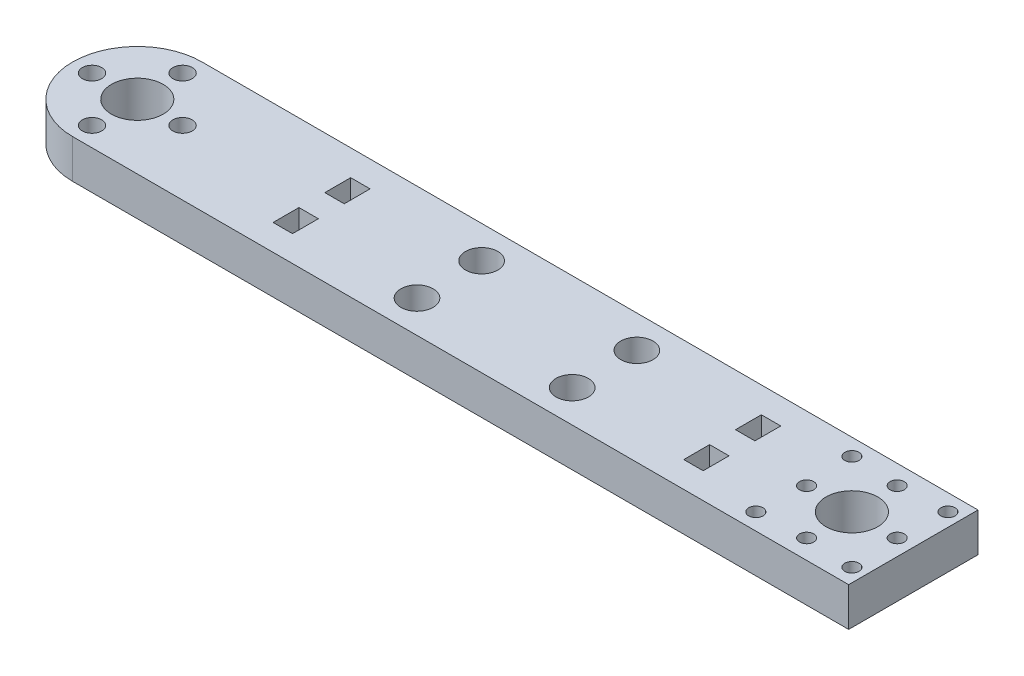
SolidWorks part; units mm, degrees
material "PF"
ref_plane "前视基准面" through (0, 0, 0) normal (0, 0, 1) x (1, 0, 0)
ref_plane "上视基准面" through (0, 0, 0) normal (0, 1, 0) x (1, 0, 0)
ref_plane "右视基准面" through (0, 0, 0) normal (1, 0, 0) x (0, 0, -1)
sketch "草图1" plane through (0, 0, 0) normal (0, 1, 0) x (1, 0, 0)
  line L1 (-41.2, 20) -> (78.8, 20)
  line L3 (-41.2, 0) -> (78.8, 0)
  line L4 (78.8, 20) -> (78.8, 0)
  arc A0 (-41.2, 20) -> (-41.2, 0) centre (-41.2, 10) ccw
  dimension "D1" = 20
  dimension "D2" = 120
extrude "凸台-拉伸1" add sketch "草图1" along normal blind 6
sketch "草图2" plane through (0, 6, 0) normal (0, 1, 0) x (1, 0, 0)
  line L0 (-41.2, 20) -> (-41.2, 0) construction
  line L1 (-41.2, 17) -> (-41.2, 3)
  circle A0 centre (-41.2, 3) radius 1.5
  circle A1 centre (-48.2, 10) radius 1.5
  circle A2 centre (-41.2, 17) radius 1.5
  circle A3 centre (-34.2, 10) radius 1.5
  circle A4 centre (-41.2, 10) radius 4
  point P7 (-41.2, 10)
  dimension "D1" = 4
extrude "切除-拉伸1" cut sketch "草图2" against normal blind 10 contours A1 | A2 L0 L1 | L0 A2 L1 | A3 | L1 L0 A0 | L0 L1 A0 | A4
sketch "草图3" plane through (0, 6, 0) normal (0, 1, 0) x (1, 0, 0)
  line L0 (-51.2, 10) -> (-14.2, 10) construction
  line L1 (-14.2, 20) -> (-14.2, 0) construction
  line L2 (78.8, 20) -> (-41.2, 20) construction
  line L3 (-41.2, 0) -> (78.8, 0) construction
  line L4 (-14.2, 12) -> (-14.2, 8)
  line L5 (-14.2, 12) -> (-14.2, 16)
  line L6 (-14.2, 12) -> (-11.2, 12)
  line L7 (-14.2, 16) -> (-11.2, 16)
  line L8 (-11.2, 12) -> (-11.2, 16)
  line L9 (-14.2, 8) -> (-14.2, 4)
  line L10 (-14.2, 8) -> (-11.2, 8)
  line L11 (-14.2, 4) -> (-11.2, 4)
  line L12 (-11.2, 8) -> (-11.2, 4)
  arc A0 (-41.2, 20) -> (-41.2, 0) centre (-41.2, 10) ccw construction
  circle A1 centre (-41.2, 10) radius 4 construction
  point P14 (-14.2, 10)
  dimension "D4" = 27
  dimension "D1" = 4
  dimension "D2" = 4
  dimension "D3" = 3
extrude "切除-拉伸2" cut sketch "草图3" against normal blind 10 contours L5 L6 L8 L7 | L9 L10 L12 L11
sketch "草图4" plane through (0, 6, 0) normal (0, 1, 0) x (1, 0, 0)
  line L0 (78.8, 10) -> (69.3, 10) construction
  line L1 (78.8, 0) -> (78.8, 20) construction
  line L2 (78.8, 20) -> (78.8, 0)
  line L3 (69.3, 10) -> (76.7246, 17.4246)
  line L4 (69.3, 10) -> (62.3, 10)
  line L5 (69.3, 17) -> (69.3, 3) construction
  line L6 (69.3, 3) -> (69.3, 10) construction
  line L7 (61.8754, 17.4246) -> (69.3, 10) construction
  line L8 (69.3, 10) -> (76.7246, 2.5754) construction
  line L9 (76.7246, 2.5754) -> (69.3, 10) construction
  line L10 (61.8754, 2.5754) -> (69.3, 10) construction
  line L11 (61.8754, 2.5754) -> (69.3, 10) construction
  line L12 (69.3, 10) -> (52.3, 10) construction
  line L13 (52.3, 20) -> (52.3, 0)
  line L14 (-41.2, 0) -> (78.8, 0) construction
  line L15 (52.3, 12) -> (52.3, 16)
  line L16 (52.3, 12) -> (49.3, 12)
  line L17 (52.3, 16) -> (49.3, 16)
  line L18 (49.3, 12) -> (49.3, 16)
  line L19 (-14.2, 12) -> (-11.2, 12) construction
  line L20 (52.3, 4) -> (49.3, 4)
  line L21 (49.3, 8) -> (49.3, 4)
  line L22 (52.3, 8) -> (49.3, 8)
  line L23 (52.3, 8) -> (52.3, 4)
  circle A0 centre (76.7246, 17.4246) radius 1.1
  circle A1 centre (76.7246, 2.5754) radius 1.1
  circle A2 centre (61.8754, 2.5754) radius 1.1
  circle A3 centre (61.8754, 17.4246) radius 1.1
  circle A4 centre (62.3, 10) radius 1.1
  circle A5 centre (69.3, 17) radius 1.1
  circle A6 centre (76.3, 10) radius 1.1
  circle A7 centre (69.3, 3) radius 1.1
  circle A8 centre (69.3, 10) radius 4
  point P29 (52.3, 10)
  dimension "D2" = 4
  dimension "D3" = 4
  dimension "D8" = 8
  dimension "D1" = 9.5
  dimension "D4" = 7
  dimension "D5" = 17
  dimension "D6" = 3
  dimension "D7" = 4
extrude "切除-拉伸4" cut sketch "草图4" against normal blind 10
sketch "草图5" plane through (0, 6, 0) normal (0, 1, 0) x (1, 0, 0)
  line L0 (49.3, 12) -> (49.3, 8) construction
  line L1 (49.3, 8) -> (49.3, 10) construction
  line L2 (49.3, 10) -> (-11.2, 10) construction
  line L3 (-11.2, 10) -> (-11.2, 12) construction
  line L4 (-11.2, 12) -> (-11.2, 8) construction
  line L5 (-11.2, 8) -> (-11.2, 10) construction
  line L6 (-11.2, 10) -> (19.05, 10) construction
  line L7 (19.05, 10) -> (19.05, 20) construction
  line L8 (78.8, 20) -> (-41.2, 20) construction
  line L9 (19.05, 20) -> (19.05, 0) construction
  line L10 (-41.2, 0) -> (78.8, 0) construction
  circle A0 centre (31.05, 5) radius 2.5
  circle A1 centre (31.05, 15) radius 2.5
  circle A2 centre (31.05, 15) radius 2.5
  circle A3 centre (31.05, 5) radius 2.5
  circle A4 centre (7.05, 5) radius 2.5
  circle A5 centre (7.05, 15) radius 2.5
  dimension "D1" = 12
  dimension "D2" = 5
extrude "切除-拉伸5" cut sketch "草图5" against normal blind 10 contours A1 | A0 | A5 | A4
